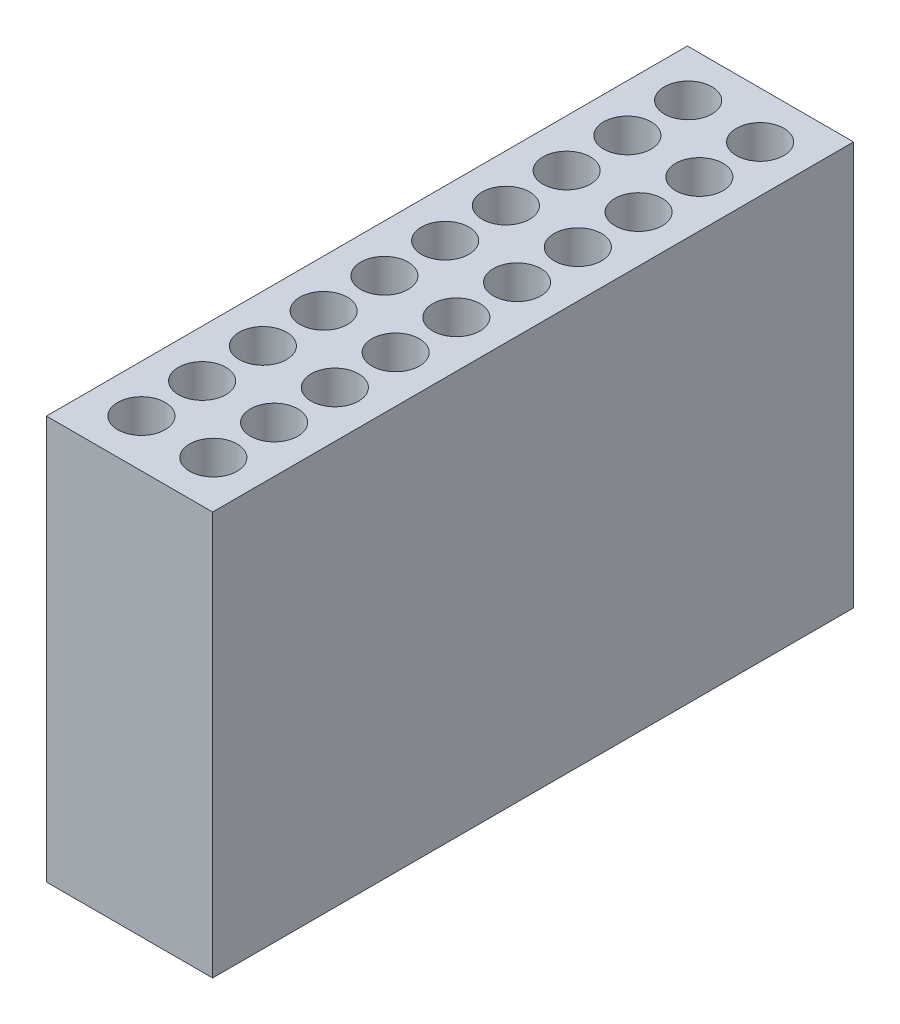
SolidWorks part; units mm, degrees
ref_plane "Front Plane" through (0, 0, 0) normal (0, 0, 1) x (1, 0, 0)
ref_plane "Top Plane" through (0, 0, 0) normal (0, 1, 0) x (1, 0, 0)
ref_plane "Right Plane" through (0, 0, 0) normal (1, 0, 0) x (0, 0, -1)
sketch "Sketch1" plane through (0, 0, 0) normal (0, 1, 0) x (1, 0, 0)
  line L1 (-0.889, -3.429) -> (0.889, -3.429)
  line L2 (-0.889, -3.429) -> (-0.889, 3.429)
  line L3 (-0.889, 3.429) -> (0.889, 3.429)
  line L4 (0.889, -3.429) -> (0.889, 3.429)
  line L5 (-0.889, -3.429) -> (0.889, 3.429) construction
  line L6 (-0.889, 3.429) -> (0.889, -3.429) construction
  point P0 (0, 0)
extrude "Boss-Extrude1" add sketch "Sketch1" along normal blind 4.318
sketch "Sketch3" plane through (0, 4.318, 0) normal (0, 1, 0) x (1, 0, 0)
  line L0 (-0.889, -3.429) -> (-0.381, -3.429) construction
  line L1 (-0.889, -3.429) -> (0.889, -3.429) construction
  line L2 (-0.381, -3.429) -> (-0.381, -2.921) construction
  circle A0 centre (-0.381, -2.921) radius 0.254
extrude "Cut-Extrude2" cut sketch "Sketch3" against normal through all
pattern_linear "LPattern2" count 10 spacing 0.65 along (0, 0, -1) count 2 spacing 0.77 along (1, 0, 0) of "Cut-Extrude2"
